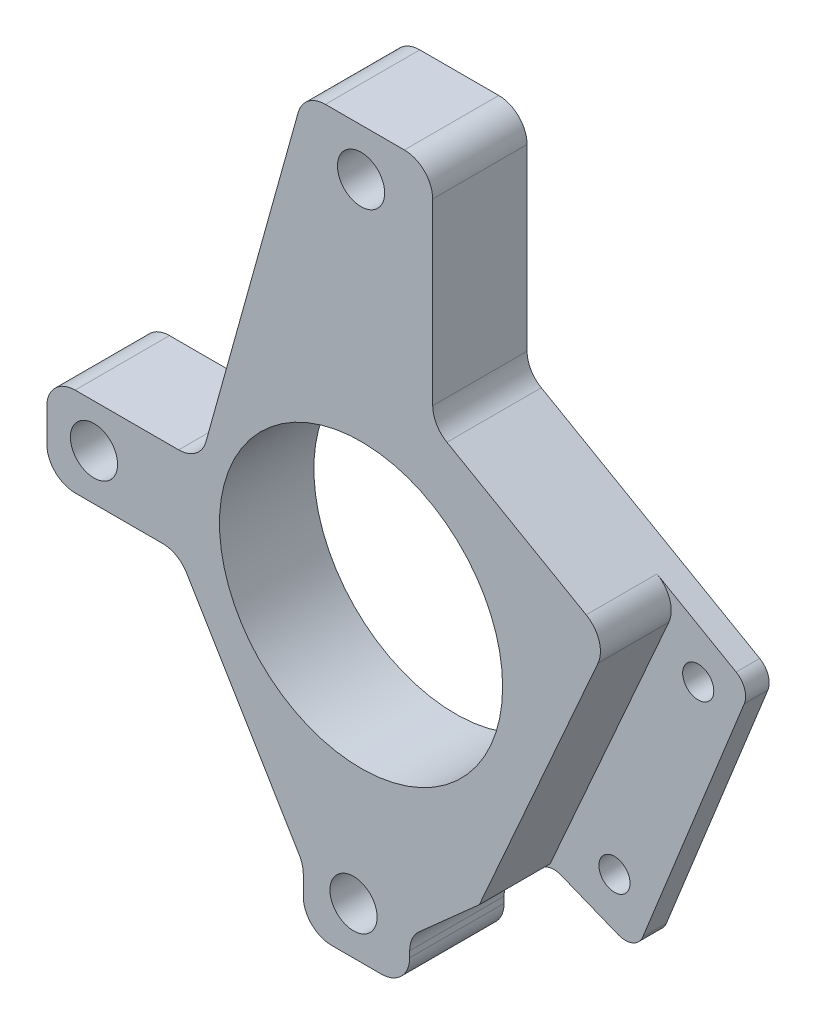
SolidWorks part; units mm, degrees
ref_plane "Front Plane" through (0, 0, 0) normal (0, 0, 1) x (1, 0, 0)
ref_plane "Top Plane" through (0, 0, 0) normal (0, 1, 0) x (1, 0, 0)
ref_plane "Right Plane" through (0, 0, 0) normal (1, 0, 0) x (0, 0, -1)
sketch "Sketch1" plane through (0, 0, 0) normal (0, 0, 1) x (1, 0, 0)
  line L0 (-15.3769, 111.8592) -> (19.2813, 111.8592)
  line L1 (19.2813, 111.8592) -> (19.2813, 51.6625)
  line L2 (19.2813, 51.6625) -> (85.7172, 13.5763)
  line L3 (85.7172, 13.5763) -> (54.8801, -63.2031)
  line L6 (13.0904, -70.6092) -> (13.0904, -83.3092)
  line L7 (13.0904, -83.3092) -> (-15.5465, -83.3092)
  line L8 (-15.5465, -83.3092) -> (-15.5465, -68.3562)
  line L9 (-15.5465, -68.3562) -> (-49.1135, -12.3821)
  line L10 (-49.1135, -12.3821) -> (-84.5631, -12.3821)
  line L11 (-84.5631, -12.3821) -> (-84.5631, 11.5981)
  line L12 (-84.5631, 11.5981) -> (-43.2846, 11.5981)
  line L13 (-43.2846, 11.5981) -> (-15.3769, 111.8592)
  line L14 (54.8801, -63.2031) -> (31.8266, -53.9441)
  line L15 (31.8266, -53.9441) -> (13.0904, -70.6092)
  circle A0 centre (0, 0) radius 38.1
  circle A3 centre (0, 99.1592) radius 6.35
  circle A4 centre (-2.0215, -70.6092) radius 6.35
  circle A5 centre (-71.8631, 0) radius 6.35
  dimension "D1" = 76.2
  dimension "D2" = 12.7
  dimension "D3" = 12.7
  dimension "D4" = 12.7
extrude "Boss-Extrude1" add sketch "Sketch1" along normal blind 25.4
sketch "Sketch2" plane through (0, 0, 25.4) normal (0, 0, 1) x (1, 0, 0)
  line L5 (85.7172, 13.5763) -> (66.5382, 24.5712)
  line L6 (85.7172, 13.5763) -> (19.2813, 51.6625) construction
  line L7 (66.5382, 24.5712) -> (31.8266, -53.9441)
extrude "Cut-Extrude1" cut sketch "Sketch2" against normal blind 19.05
sketch "Sketch3" plane through (0, 0, 25.4) normal (0, 0, 1) x (1, 0, 0)
  circle A0 centre (71.6792, 8.3618) radius 4.191
  circle A1 centre (49.1489, -47.7348) radius 4.191
  dimension "D1" = 8.382
  dimension "D2" = 8.382
  dimension "D3" = 60.452
extrude "Cut-Extrude2" cut sketch "Sketch3" against normal through all
fillet "Fillet1" radius 7.62 12 edges at (-15.3769, 111.8592, 12.7) (19.2813, 111.8592, 12.7) (19.2813, 51.6625, 12.7) (66.5382, 24.5712, 15.875) (13.0904, -70.6092, 12.7) (13.0904, -83.3092, 12.7) (-15.5465, -83.3092, 12.7) (-15.5465, -68.3562, 12.7) (-49.1135, -12.3821, 12.7) (-84.5631, -12.3821, 12.7) (-84.5631, 11.5981, 12.7) (-43.2846, 11.5981, 12.7)
fillet "Fillet2" radius 5.08 3 edges at (31.8266, -53.9441, 3.175) (54.8801, -63.2031, 3.175) (85.7172, 13.5763, 3.175)
